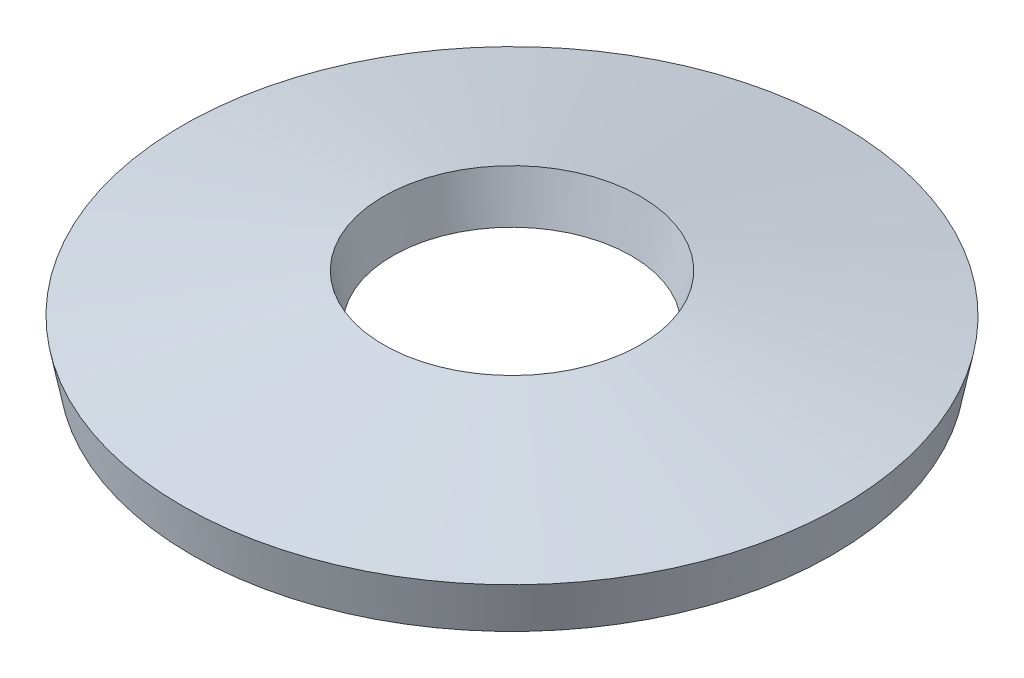
SolidWorks part; units mm, degrees
ref_plane "Front" through (0, 0, 0) normal (0, 0, 1) x (1, 0, 0)
ref_plane "Top" through (0, 0, 0) normal (0, 1, 0) x (1, 0, 0)
ref_plane "Right" through (0, 0, 0) normal (1, 0, 0) x (0, 0, -1)
sketch "Sketch1" plane through (0, 0, 0) normal (0, 0, 1) x (1, 0, 0)
  line L0 (8.5206, 0) -> (3.175, 1.0393)
  line L1 (3.175, 1.0393) -> (3.4174, 2.286)
  line L2 (3.4174, 2.286) -> (8.763, 1.2467)
  line L3 (8.763, 1.2467) -> (8.5206, 0)
  line L4 (0, 0) -> (0, 2.286) construction
  point P5 (3.2962, 1.6627)
  dimension "D1" = 5.4457
  dimension "ID" = 6.35
  dimension "OD" = 17.526
  dimension "Thickness" = 1.27
  dimension "Height" = 2.286
revolve "Revolve1" add sketch "Sketch1" angle 360 about L4
sketch "Sketch15" plane through (0, 0, 0) normal (0, 1, 0) x (1, 0, 0)
  circle A0 centre (0, 0) radius 8.763
  circle A1 centre (0, 0) radius 3.175
